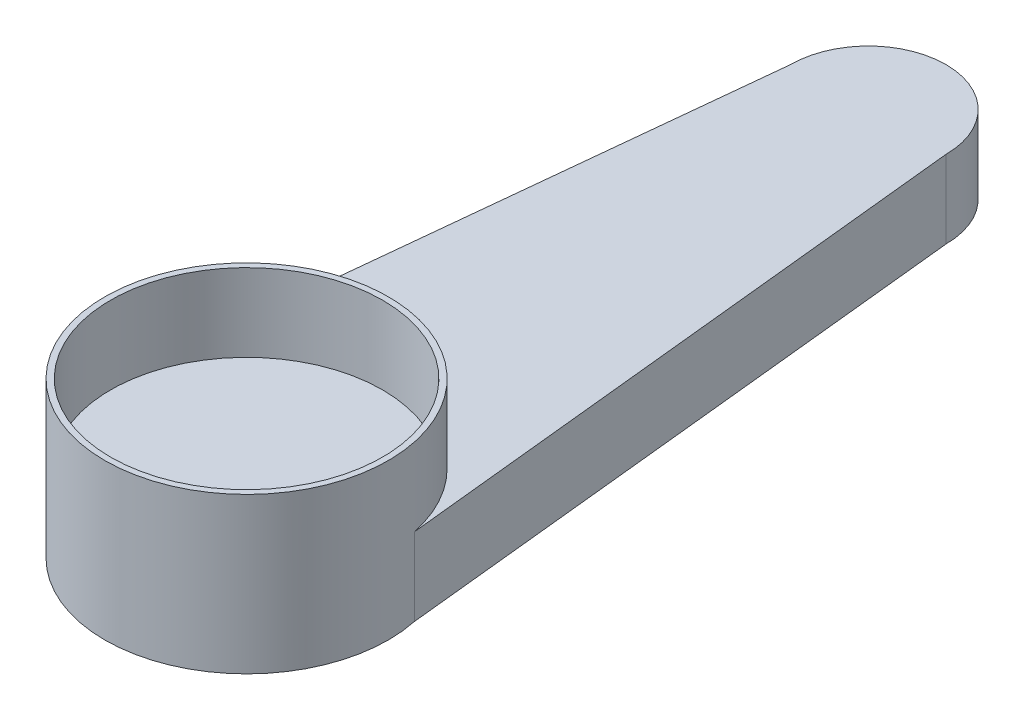
SolidWorks part; units mm, degrees
ref_plane "Front Plane" through (0, 0, 0) normal (0, 0, 1) x (1, 0, 0)
ref_plane "Top Plane" through (0, 0, 0) normal (0, 1, 0) x (1, 0, 0)
ref_plane "Right Plane" through (0, 0, 0) normal (1, 0, 0) x (0, 0, -1)
sketch "Sketch1" plane through (0, 0, 0) normal (0, 1, 0) x (1, 0, 0)
  line L2 (0, -8) -> (0, 8) construction
  line L3 (-3.5732, -7.2551) -> (-2, 8)
  line L4 (3.5732, -7.2551) -> (2, 8)
  arc A4 (-3.5732, -7.2551) -> (3.5732, -7.2551) centre (0, -8) ccw
  arc A5 (2, 8) -> (-2, 8) centre (0, 8) ccw
  point P4 (0, 0)
  point P5 (0, 0)
  point P7 (0, 0)
  point P9 (0, 0)
  point P11 (0, 0)
  point P12 (0, 0)
  point P13 (0, 0)
  dimension "D1" = 7.3
  dimension "D2" = 4
  dimension "D4" = 7.1464
  dimension "D3" = 3.5732
  dimension "D5" = 3.6307
extrude "Boss-Extrude1" add sketch "Sketch1" against normal blind 2 contours L4 A5 L3 A4
sketch "Sketch2" plane through (0, 0, 0) normal (0, 1, 0) x (1, 0, 0)
  circle A0 centre (0, -8) radius 3.65
  dimension "D1" = 7.3
extrude "Boss-Extrude2" add sketch "Sketch2" along normal blind 2
sketch "Sketch3" plane through (0, 2, 0) normal (0, 1, 0) x (1, 0, 0)
  circle A0 centre (0, -8) radius 3.5
  dimension "D1" = 7
extrude "Cut-Extrude1" cut sketch "Sketch3" against normal blind 2
